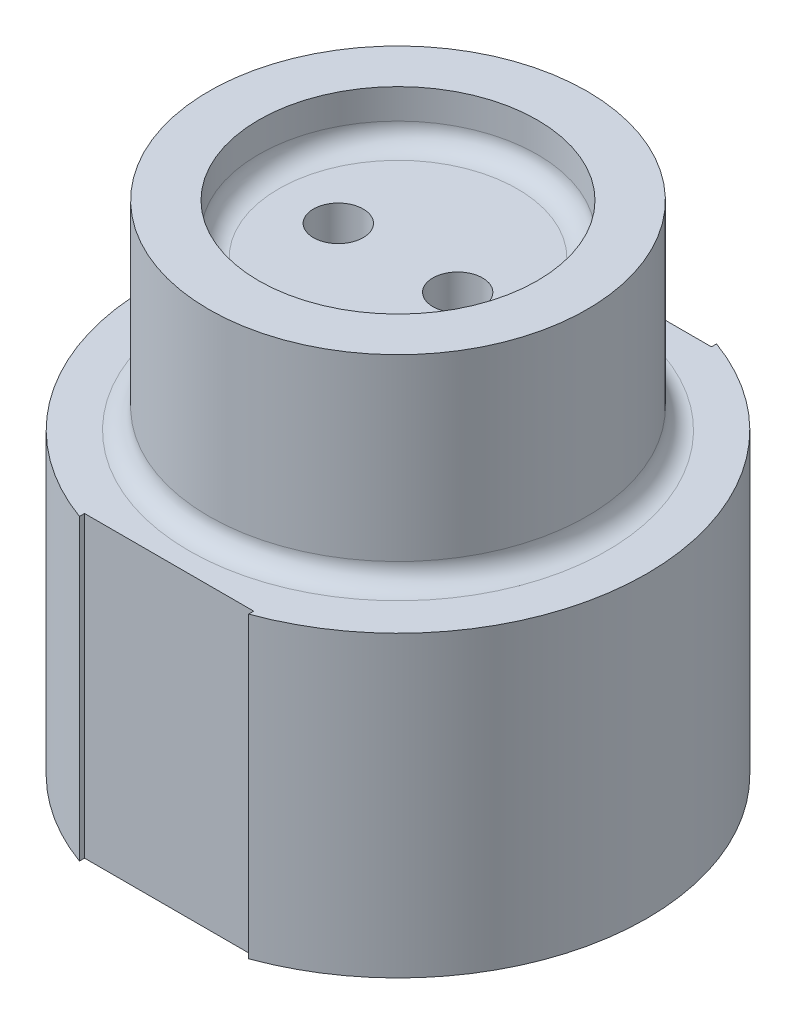
SolidWorks part; units mm, degrees
ref_plane "Front Plane" through (0, 0, 0) normal (0, 0, 1) x (1, 0, 0)
ref_plane "Top Plane" through (0, 0, 0) normal (0, 1, 0) x (1, 0, 0)
ref_plane "Right Plane" through (0, 0, 0) normal (1, 0, 0) x (0, 0, -1)
sketch "Sketch1" plane through (0, 0, 0) normal (0, 0, 1) x (1, 0, 0)
  line L0 (0, 0) -> (63.5, 0)
  line L1 (63.5, 0) -> (63.5, 76.2)
  line L2 (63.5, 76.2) -> (48.26, 76.2)
  line L3 (48.26, 76.2) -> (48.26, 127)
  line L4 (0, 12.7) -> (50.8, 12.7)
  line L5 (50.8, 12.7) -> (50.8, 63.5)
  line L6 (50.8, 63.5) -> (35.56, 63.5)
  line L7 (35.56, 63.5) -> (35.56, 127)
  line L8 (35.56, 127) -> (48.26, 127)
  line L9 (0, 12.7) -> (0, 0)
  line L10 (0, 0) -> (0, 133.4959) construction
  dimension "D1" = 63.5
  dimension "D2" = 76.2
  dimension "D3" = 50.8
  dimension "D4" = 15.24
  dimension "D5" = 12.7
revolve "Revolve1" add sketch "Sketch1" angle 360 about L10
ref_plane "Plane1" through (0, 114.3, 0) normal (0, 1, 0) x (1, 0, 0)
sketch "Sketch2" plane through (0, 114.3, 0) normal (0, 1, 0) x (1, 0, 0)
  circle A0 centre (0, 0) radius 35.56
  circle A1 centre (0, 0) radius 35.56 construction
extrude "Boss-Extrude1" add sketch "Sketch2" against normal blind 5.08
sketch "Sketch3" plane through (0, 114.3, 0) normal (0, 1, 0) x (1, 0, 0)
  circle A0 centre (15.24, 0) radius 6.35
  circle A1 centre (15.24, 0) radius 8.89
  dimension "D2" = 12.7
  dimension "D1" = 15.24
  dimension "D3" = 2.54
sketch "Sketch4" plane through (0, 0, 0) normal (0, 0, 1) x (1, 0, 0)
  line L0 (15.24, 114.3) -> (15.24, 50.8)
  line L1 (24.13, 114.3) -> (6.35, 114.3) construction
  line L2 (15.24, 50.8) -> (33.02, 50.8)
  line L3 (33.02, 50.8) -> (33.02, 12.7)
  line L4 (50.8, 12.7) -> (-50.8, 12.7) construction
  line L6 (-63.5, 0) -> (63.5, 0) construction
  dimension "D1" = 50.8
  dimension "D2" = 63.5
  dimension "D3" = 17.78
sweep "Sweep1" add profiles "Sketch3" path "Sketch4"
sketch "Sketch5" plane through (0, 12.7, 0) normal (0, 1, 0) x (1, 0, 0)
  circle A0 centre (33.02, 0) radius 6.35
  circle A1 centre (33.02, 0) radius 6.35 construction
extrude "Cut-Extrude1" cut sketch "Sketch5" against normal through all
sketch "Sketch6" plane through (0, 109.22, 0) normal (0, -1, 0) x (1, 0, 0)
  circle A0 centre (15.24, 0) radius 6.35
  circle A1 centre (15.24, 0) radius 6.35 construction
extrude "Cut-Extrude2" cut sketch "Sketch6" against normal through all
mirror "Mirror1" about plane through (0, 0, 0) normal (1, 0, 0) of "Cut-Extrude2", "Cut-Extrude1", "Sweep1"
ref_plane "Plane2" through (0, 0, 63.5) normal (0, 0, 1) x (1, 0, 0)
sketch "Sketch7" plane through (0, 0, 63.5) normal (0, 0, 1) x (1, 0, 0)
  line L0 (-63.5, 0) -> (63.5, 0) construction
  line L1 (-21.59, 0) -> (21.59, 0)
  line L2 (-21.59, 0) -> (-21.59, 76.2)
  line L3 (-21.59, 76.2) -> (21.59, 76.2)
  line L4 (21.59, 0) -> (21.59, 76.2)
  line L5 (63.5, 76.2) -> (-63.5, 76.2) construction
  dimension "D1" = 43.18
extrude "Cut-Extrude3" cut sketch "Sketch7" against normal blind 5.08
mirror "Mirror2" about plane through (0, 0, 0) normal (0, 0, 1) of "Cut-Extrude3"
fillet "Fillet1" radius 5.08 2 edges at (0, 114.3, 35.56) (0, 76.2, -48.26)
